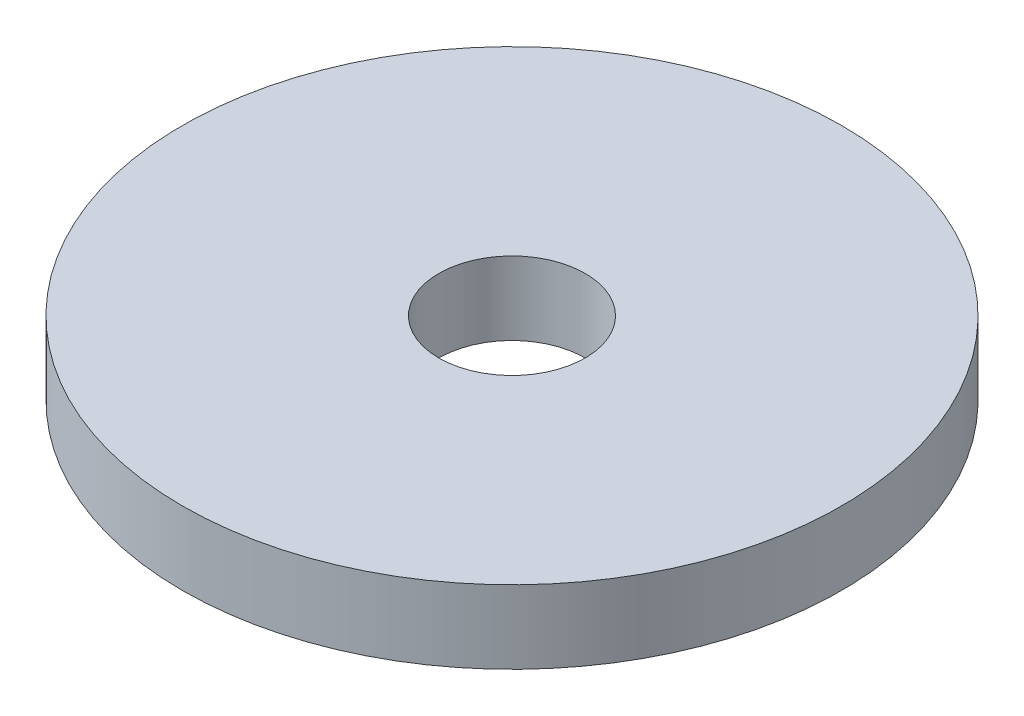
SolidWorks part; units mm, degrees
ref_plane "前视基准面" through (0, 0, 0) normal (0, 0, 1) x (1, 0, 0)
ref_plane "上视基准面" through (0, 0, 0) normal (0, 1, 0) x (1, 0, 0)
ref_plane "右视基准面" through (0, 0, 0) normal (1, 0, 0) x (0, 0, -1)
sketch "草图1" plane through (0, 0, 0) normal (0, 1, 0) x (1, 0, 0)
  circle A0 centre (0, 0) radius 9
  circle A1 centre (0, 0) radius 2
  dimension "D1" = 18
  dimension "D2" = 4
extrude "凸台-拉伸1" add sketch "草图1" along normal blind 2
